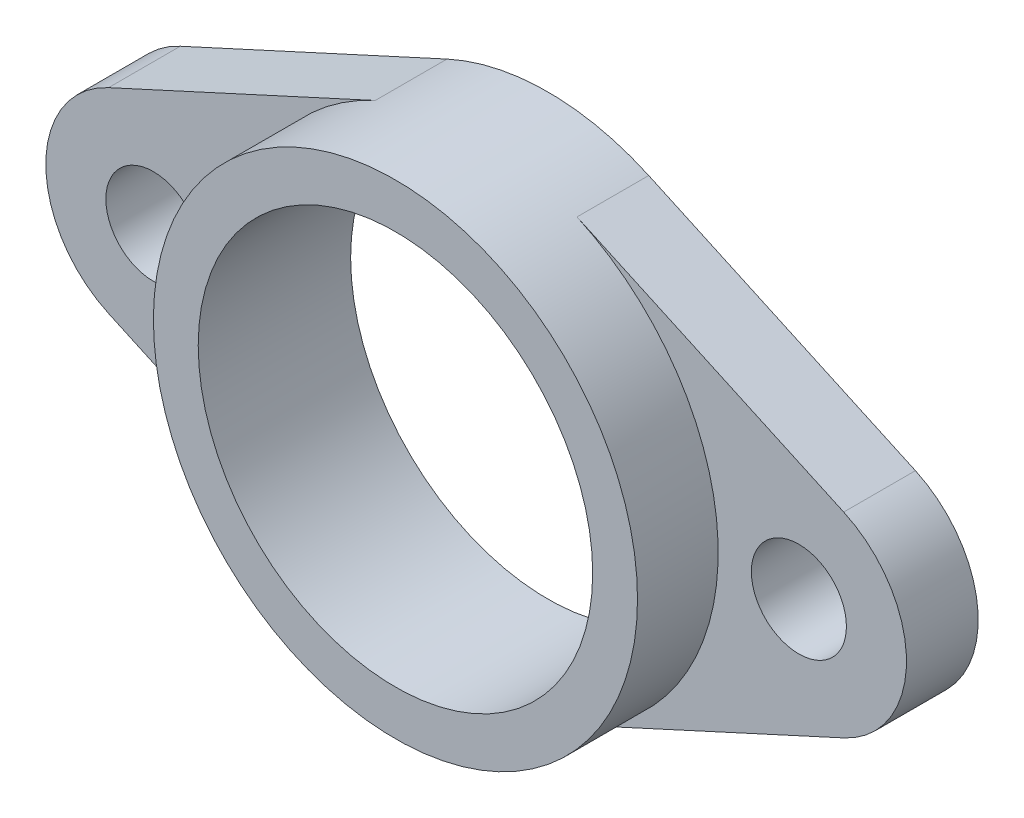
SolidWorks part; units mm, degrees
ref_plane "Front Plane" through (0, 0, 0) normal (0, 0, 1) x (1, 0, 0)
ref_plane "Top Plane" through (0, 0, 0) normal (0, 1, 0) x (1, 0, 0)
ref_plane "Right Plane" through (0, 0, 0) normal (1, 0, 0) x (0, 0, -1)
sketch "Layout Sketch" plane through (0, 0, 0) normal (0, 0, 1) x (1, 0, 0)
  line L0 (0, 0) -> (0, 14.778) construction
  circle A0 centre (-18, 0) radius 1 construction
  circle A1 centre (18, 0) radius 1 construction
  point P4 (0, 0)
  point P6 (0, 70.694)
  point P7 (0, 243.7359)
  point P8 (0, 352.557)
  point P11 (0, 53.5762)
  point P12 (0, 14.778)
  dimension "D1" = 2
  dimension "D2" = 18
sketch "Base Sketch" plane through (0, 0, 0) normal (0, 0, 1) x (1, 0, 0)
  line L0 (-20.5, 5.4544) -> (-5.625, 12.2723)
  line L1 (-20.5, -5.4544) -> (-5.625, -12.2723)
  line L2 (5.625, 12.2723) -> (20.5, 5.4544)
  line L3 (20.5, -5.4544) -> (5.625, -12.2723)
  line L4 (0, 0) -> (7.7453, 0) construction
  arc A0 (-20.5, 5.4544) -> (-20.5, -5.4544) centre (-18, 0) ccw
  arc A1 (20.5, -5.4544) -> (20.5, 5.4544) centre (18, 0) ccw
  arc A2 (-5.625, -12.2723) -> (5.625, -12.2723) centre (0, 0) ccw
  arc A3 (5.625, 12.2723) -> (-5.625, 12.2723) centre (0, 0) ccw
  circle A4 centre (0, 0) radius 11
  dimension "D1" = 27
  dimension "D2" = 6
  dimension "D3" = 22
extrude "Base Extrude" add sketch "Base Sketch" along normal blind 4
sketch "Bearing Retaining Ring Sketch" plane through (0, 0, 0) normal (0, 0, 1) x (1, 0, 0)
  circle A0 centre (0, 0) radius 11
  circle A1 centre (0, 0) radius 13.5
  arc A2 (5.625, 12.2723) -> (-5.625, 12.2723) centre (0, 0) ccw construction
  circle A3 centre (0, 0) radius 11 construction
extrude "Bearing Retaining Ring" add sketch "Bearing Retaining Ring Sketch" along normal blind 8.5
hole_wizard "Mounting Holes" positions "Mounting Holes Position Sketch" profile "Mounting Holes Profile Sketch" hole size "M5" standard "ANSI Metric" end condition up to next
sketch "Mounting Holes Position Sketch" plane through (0, 0, 0) normal (0, 0, -1) x (-1, 0, 0)
  point P0 (18, 0)
  point P3 (-18, 0)
sketch "Mounting Holes Profile Sketch" plane through (-18, 0, 0) normal (1, 0, 0) x (0, 1, 0)
  line L0 (0, 0) -> (0, 4)
  line L1 (0, 4) -> (2.65, 4)
  line L2 (2.65, 4) -> (2.65, 0)
  line L5 (2.65, 0) -> (0, 0)
  line L11 (0, -6.35) -> (0, 107.95) construction
  dimension "Thru Hole Dia." = 5.3
  dimension "Thru Hole Depth" = 4
